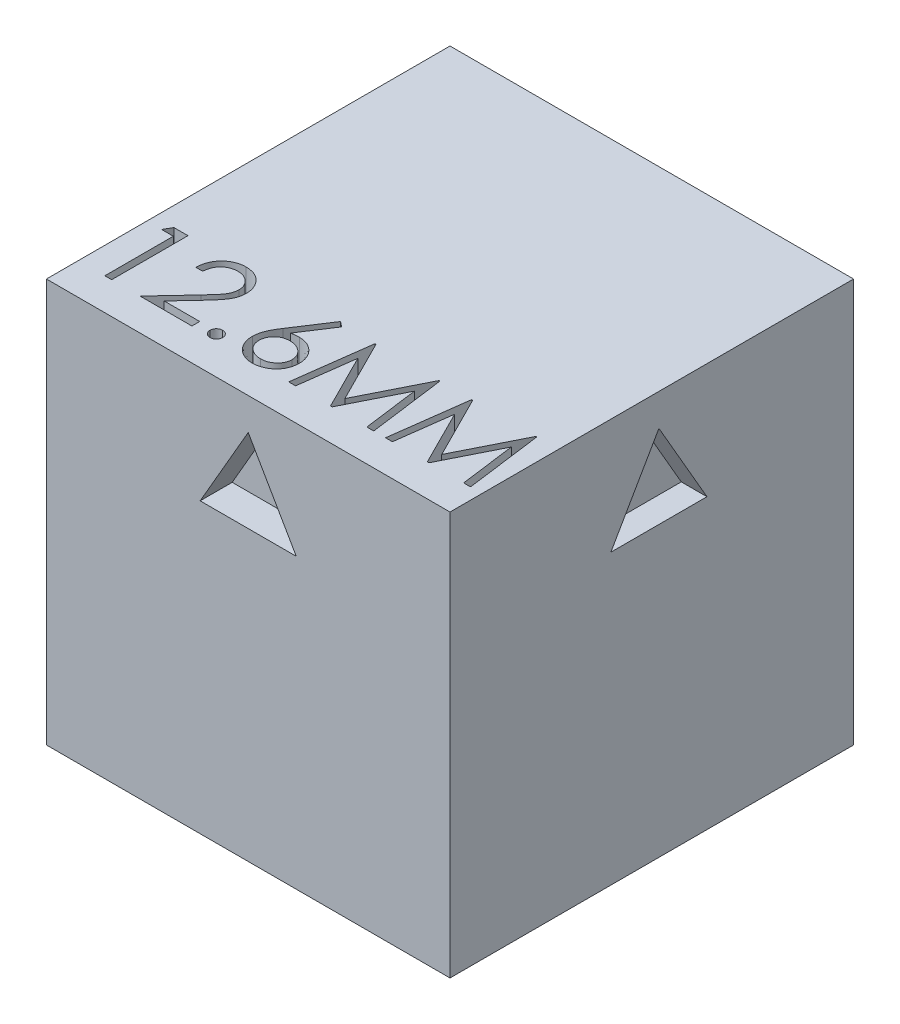
SolidWorks part; units mm, degrees
ref_plane "Alzado" through (0, 0, 0) normal (0, 0, 1) x (1, 0, 0)
ref_plane "Planta" through (0, 0, 0) normal (0, 1, 0) x (1, 0, 0)
ref_plane "Vista lateral" through (0, 0, 0) normal (1, 0, 0) x (0, 0, -1)
sketch "Croquis1" plane through (0, 0, 0) normal (0, 0, 1) x (1, 0, 0)
  line L1 (-6.3, 6.3) -> (6.3, 6.3)
  line L2 (-6.3, 6.3) -> (-6.3, -6.3)
  line L3 (-6.3, -6.3) -> (6.3, -6.3)
  line L4 (6.3, 6.3) -> (6.3, -6.3)
  line L5 (-6.3, 6.3) -> (6.3, -6.3) construction
  line L6 (-6.3, -6.3) -> (6.3, 6.3) construction
  point P0 (0, 0)
  dimension "D1" = 12.6
  dimension "D2" = 12.6
extrude "Saliente-Extruir1" add sketch "Croquis1" along normal blind 12.6
sketch "Croquis3" plane through (0, 6.3, 0) normal (0, 1, 0) x (1, 0, 0)
  line L0 (-6.3, -11.6) -> (6.3, -11.6) construction
  line L1 (-6.3, -12.6) -> (-6.3, 0) construction
  line L2 (6.3, -12.6) -> (6.3, 0) construction
  line L3 (6.3, -12.6) -> (-6.3, -12.6) construction
  dimension "D1" = 1
sketch "Croquis2" plane through (0, 6.3, 0) normal (0, 1, 0) x (1, 0, 0)
  text T0 "12.6MM" font "Century Gothic" height in points 9
extrude "Cortar-Extruir1" cut sketch "Croquis2" against normal blind 1
sketch "Croquis4" plane through (0, 0, 12.6) normal (0, 0, 1) x (1, 0, 0)
  line L0 (0, 5.3) -> (-1.5, 2.7019)
  line L1 (-1.5, 2.7019) -> (1.5, 2.7019)
  line L2 (1.5, 2.7019) -> (0, 5.3)
  line L3 (0, 0) -> (0, 2.7019) construction
  line L4 (0, 2.7019) -> (0, 5.3) construction
  point P3 (0, 0)
  dimension "D1" = 1
  dimension "D2" = 3
  dimension "D3" = 3
extrude "Cortar-Extruir2" cut sketch "Croquis4" against normal blind 1
pattern_circular "MatrizC1" count 4 over 360 about axis through (-0.0122, 0, 6.0897) along (0, 1, 0) of "Cortar-Extruir2"
